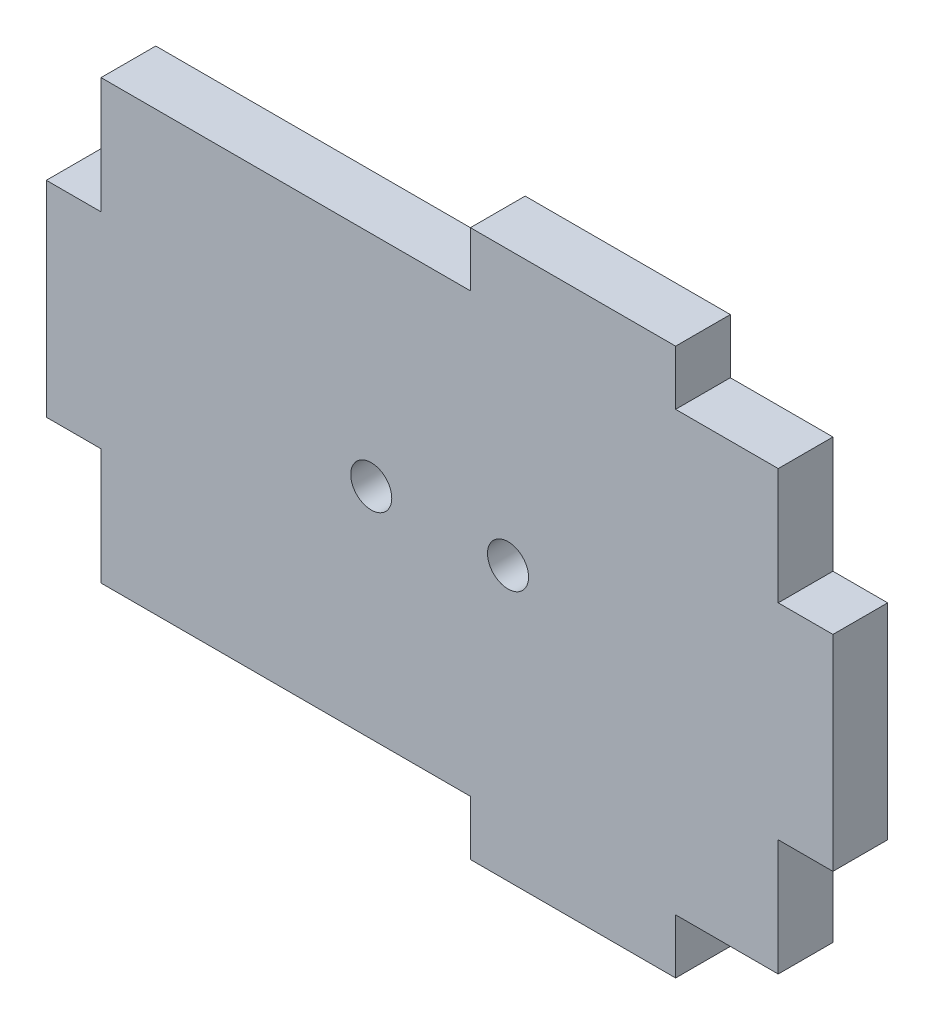
SolidWorks part; units mm, degrees
ref_plane "Спереди" through (0, 0, 0) normal (0, 0, 1) x (1, 0, 0)
ref_plane "Сверху" through (0, 0, 0) normal (0, 1, 0) x (1, 0, 0)
ref_plane "Справа" through (0, 0, 0) normal (1, 0, 0) x (0, 0, -1)
other "Configuration Table"
sketch "Эскиз1" plane through (0, 0, 0) normal (0, 0, 1) x (1, 0, 0)
  line L0 (27, 32) -> (27, 36)
  line L1 (0, 0) -> (27, 0)
  line L2 (0, 0) -> (0, 8.5)
  line L3 (0, 32) -> (27, 32)
  line L4 (49.5, 0) -> (49.5, 8.5)
  line L5 (27, 36) -> (42, 36)
  line L6 (42, 36) -> (42, 32)
  line L7 (42, 32) -> (49.5, 32)
  line L8 (0, 16) -> (44.3, 16) construction
  line L9 (24.75, 0) -> (24.75, 32) construction
  line L10 (42, -4) -> (42, 0)
  line L11 (27, -4) -> (42, -4)
  line L12 (27, 0) -> (27, -4)
  line L13 (42, 0) -> (49.5, 0)
  line L14 (49.5, 23.5) -> (53.5, 23.5)
  line L15 (53.5, 23.5) -> (53.5, 8.5)
  line L16 (49.5, 8.5) -> (53.5, 8.5)
  line L17 (0, 8.5) -> (-4, 8.5)
  line L18 (-4, 23.5) -> (-4, 8.5)
  line L19 (0, 23.5) -> (-4, 23.5)
  line L20 (0, 23.5) -> (0, 32)
  line L21 (49.5, 23.5) -> (49.5, 32)
  circle A0 centre (19.75, 16) radius 1.5
  circle A1 centre (29.75, 16) radius 1.5
  point P21 (53.5, 16)
  point P22 (-4, 16)
  dimension "D8" = 3
  dimension "D1" = 49.5
  dimension "D2" = 32
  dimension "D3" = 15
  dimension "D4" = 27
  dimension "D5" = 4
  dimension "D6" = 4
  dimension "D7" = 15
  dimension "D9" = 10
extrude "Бобышка-Вытянуть1" add sketch "Эскиз1" along normal blind 4
